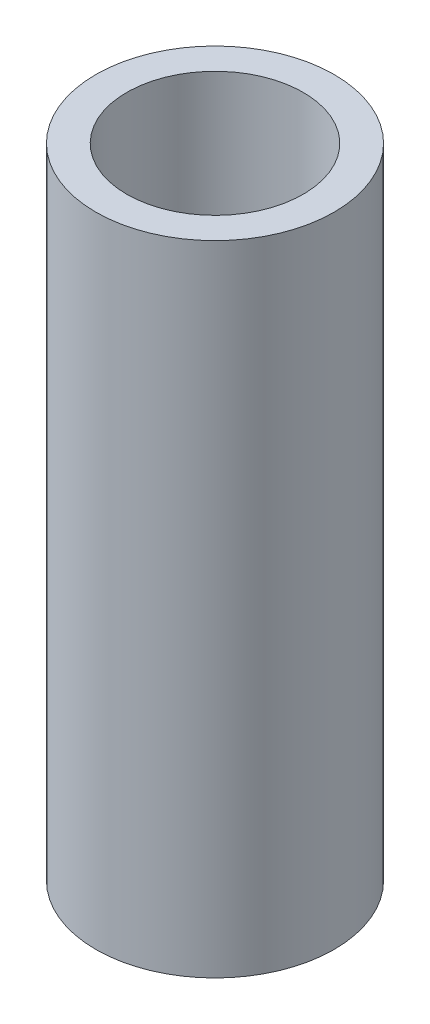
SolidWorks part; units mm, degrees
ref_plane "Front Plane" through (0, 0, 0) normal (0, 0, 1) x (1, 0, 0)
ref_plane "Top Plane" through (0, 0, 0) normal (0, 1, 0) x (1, 0, 0)
ref_plane "Right Plane" through (0, 0, 0) normal (1, 0, 0) x (0, 0, -1)
sketch "Schedule40Tube" plane through (0, 0, 0) normal (0, 1, 0) x (1, 0, 0)
  circle A0 centre (0, 0) radius 7.8994
  circle A1 centre (0, 0) radius 10.668
  dimension "D1" = 21.336
  dimension "D2" = 15.7988
extrude "Schedule40TubeLength" add sketch "Schedule40Tube" along normal blind 57.15
sketch "Sketch1" [suppressed] plane through (0, 0, 0) normal (0, 1, 0) x (1, 0, 0)
  circle A0 centre (0, 0) radius 6.35
  circle A1 centre (0, 0) radius 10.6182 construction
  circle A2 centre (0, 0) radius 14.2875
  dimension "D1" = 28.575
  dimension "D2" = 12.7
extrude "Bearing" [suppressed] add sketch "Sketch1" along normal blind 10.3187
sketch "Sketch2" [suppressed] plane through (0, 10.3187, 0) normal (0, 1, 0) x (1, 0, 0)
  line L0 (6.35, 0) -> (14.2875, 0) construction
  circle A0 centre (0, 0) radius 10.3187
  circle A1 centre (0, 0) radius 6.35 construction
  circle A2 centre (0, 0) radius 6.35 construction
  circle A3 centre (0, 0) radius 14.2875 construction
  circle A4 centre (0, 0) radius 14.2875 construction
  point P11 (10.3187, 0)
split line "Split Line1" [suppressed]
sketch "Sketch3" [suppressed] plane through (0, 10.3187, 0) normal (0, 1, 0) x (1, 0, 0)
  circle A0 centre (0, 0) radius 10.668
  dimension "D1" = 21.336
extrude "Cut-Extrude1" [suppressed] cut sketch "Sketch3" against normal through all
hole_wizard "Ø3.0 (3) Diameter Hole1" [suppressed] positions "Sketch4" profile "Sketch5" hole size "Ø3.0" standard "ANSI Metric"
sketch "Sketch4" plane through (0, 10.3187, 0) normal (0, 1, 0) x (1, 0, 0)
  point P7 (0, 12.5088)
  point P9 (0, -12.7237)
sketch "Sketch5" plane through (0, 10.3187, -12.5088) normal (1, 0, 0) x (0, 0, 1)
  line L0 (0, 0) -> (0, 10.3187)
  line L1 (0, 10.3187) -> (1.5, 10.3187)
  line L2 (1.5, 10.3187) -> (1.5, 0.025)
  line L3 (1.5, 0.025) -> (1.525, 0)
  line L5 (1.525, 0) -> (0, 0)
  line L6 (-1.5, 0.025) -> (-1.525, 0) construction
  line L11 (0, -6.35) -> (0, 107.95) construction
  dimension "Thru Hole Dia." = 3
  dimension "Thru Hole Depth" = 10.3187
  dimension "Near C'Sink Dia." = 3.05
  dimension "Near C'Sink Angle" = 90
equation "\"drill_out\"= 0.840"
equation "\"D1@Sketch3\"=\"drill_out\""
